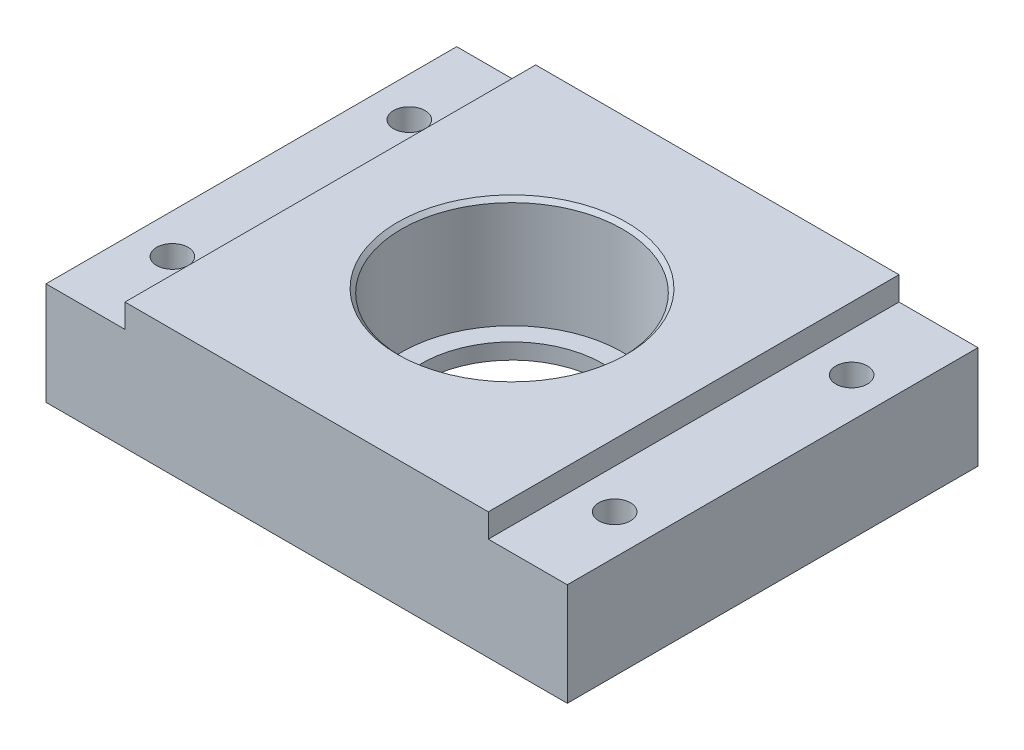
SolidWorks part; units mm, degrees
material "6063-O"
ref_plane "Front" through (0, 0, 0) normal (0, 0, 1) x (1, 0, 0)
ref_plane "Top" through (0, 0, 0) normal (0, 1, 0) x (1, 0, 0)
ref_plane "Right" through (0, 0, 0) normal (1, 0, 0) x (0, 0, -1)
sketch "草图1" plane through (0, 0, 0) normal (0, 1, 0) x (1, 0, 0)
  line L1 (25, -26) -> (-25, -26)
  line L2 (25, -26) -> (25, 26)
  line L3 (25, 26) -> (-25, 26)
  line L4 (-25, -26) -> (-25, 26)
  line L5 (25, -26) -> (-25, 26) construction
  line L6 (25, 26) -> (-25, -26) construction
  circle A0 centre (0, 0) radius 14
  dimension "D1" = 28
  dimension "D2" = 52
  dimension "D3" = 50
extrude "凸台-拉伸1" add sketch "草图1" along normal blind 16
sketch "草图2" plane through (0, 0, 0) normal (0, -1, 0) x (1, 0, 0)
  circle A0 centre (0, 0) radius 14
  circle A1 centre (0, 0) radius 11.5
  dimension "D1" = 23
extrude "凸台-拉伸2" add sketch "草图2" against normal blind 2
sketch "草图3" plane through (0, 0, -26) normal (0, 0, -1) x (-1, 0, 0)
  line L0 (-25, 0) -> (-33, 0)
  line L1 (-33, 0) -> (-33, 13)
  line L2 (-33, 13) -> (-25, 13)
  line L3 (-25, 16) -> (-25, 0) construction
  line L4 (-25, 13) -> (-25, 0)
  line L5 (0, 0) -> (0, 16) construction
  line L6 (-25, 16) -> (25, 16) construction
  line L7 (25, 13) -> (25, 0)
  line L8 (33, 13) -> (25, 13)
  line L9 (33, 0) -> (33, 13)
  line L10 (25, 0) -> (33, 0)
  dimension "D1" = 8
  dimension "D2" = 13
extrude "凸台-拉伸3" add sketch "草图3" against normal up to surface (52 mm away) up to face at (0, 8, 26)
sketch "草图4" plane through (0, 13, 0) normal (0, 1, 0) x (1, 0, 0)
  line L0 (28, 26) -> (28, -26) construction
  line L3 (-28, 26) -> (-28, -26) construction
  line L6 (-28, 0) -> (28, 0) construction
  line L7 (-33, -26) -> (-33, 26) construction
  line L9 (33, -26) -> (33, 26) construction
  line L10 (-25, -26) -> (-33, -26) construction
  line L11 (-33, 26) -> (-25, 26) construction
  circle A0 centre (-28, 15) radius 2
  circle A1 centre (-28, -15) radius 2
  circle A2 centre (28, 15) radius 2
  circle A3 centre (28, -15) radius 2
  dimension "D1" = 4
  dimension "D2" = 4
  dimension "D3" = 4
  dimension "D4" = 4
  dimension "D5" = 15
  dimension "D6" = 5
  dimension "D7" = 5
extrude "切除-拉伸1" cut sketch "草图4" against normal through all
chamfer "倒角1" distance 0.5 angle 45 1 edges at (0, 16, 14)
sketch "草图5" plane through (0, 0, 26) normal (0, 0, 1) x (1, 0, 0)
  line L0 (-25, 16) -> (25, 16) construction
  line L1 (-25, 13) -> (-23, 13)
  line L2 (-25, 13) -> (-25, 16)
  line L3 (-25, 16) -> (-23, 16)
  line L4 (-23, 13) -> (-23, 16)
  line L6 (25, 13) -> (23, 13)
  line L7 (25, 13) -> (25, 16)
  line L8 (25, 16) -> (23, 16)
  line L9 (23, 13) -> (23, 16)
  dimension "D1" = 2
  dimension "D2" = 2
extrude "切除-拉伸2" cut sketch "草图5" against normal through all
